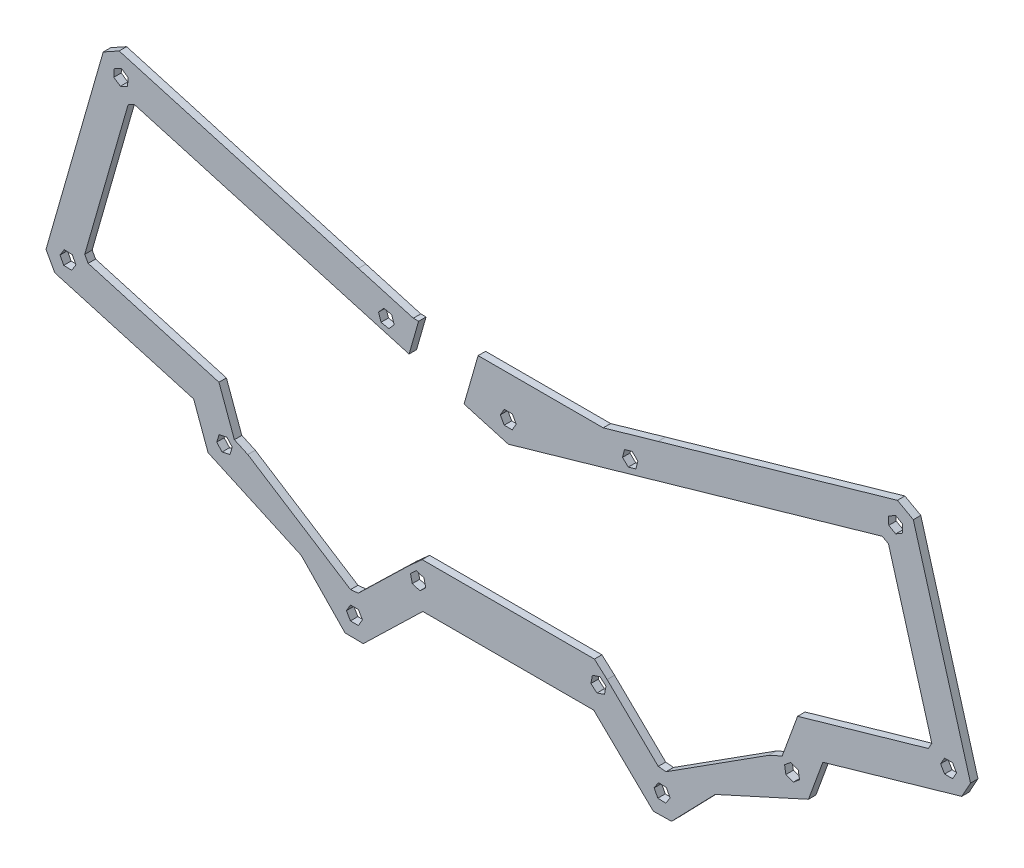
SolidWorks part; units mm, degrees
ref_plane "Plan de face" through (0, 0, 0) normal (0, 0, 1) x (1, 0, 0)
ref_plane "Plan de dessus" through (0, 0, 0) normal (0, 1, 0) x (1, 0, 0)
ref_plane "Plan de droite" through (0, 0, 0) normal (1, 0, 0) x (0, 0, -1)
sketch "Esquisse1" plane through (0, 0, 0) normal (0, 0, 1) x (1, 0, 0)
  line L0 (-121.6461, -32.0475) -> (-108.1875, -28.1884) construction
  line L1 (-108.1875, -28.1884) -> (-104.3283, -41.647) construction
  line L2 (-104.3283, -41.647) -> (-117.7869, -45.5062) construction
  line L3 (-117.7869, -45.5062) -> (-121.6461, -32.0475) construction
  line L4 (-100.1763, -37.9855) -> (-104.0355, -24.5269) construction
  line L5 (-104.0355, -24.5269) -> (-90.5769, -20.6677) construction
  line L6 (-90.5769, -20.6677) -> (-86.7177, -34.1263) construction
  line L7 (-86.7177, -34.1263) -> (-100.1763, -37.9855) construction
  line L8 (-82.5657, -30.4649) -> (-86.4249, -17.0063) construction
  line L9 (-86.4249, -17.0063) -> (-72.9663, -13.1471) construction
  line L10 (-72.9663, -13.1471) -> (-69.1071, -26.6057) construction
  line L11 (-69.1071, -26.6057) -> (-82.5657, -30.4649) construction
  line L12 (-63.6458, -27.5106) -> (-67.505, -14.0519) construction
  line L13 (-67.505, -14.0519) -> (-54.0463, -10.1927) construction
  line L14 (-54.0463, -10.1927) -> (-50.1872, -23.6514) construction
  line L15 (-50.1872, -23.6514) -> (-63.6458, -27.5106) construction
  line L16 (-44.0711, -26.8394) -> (-47.9303, -13.3808) construction
  line L17 (-47.9303, -13.3808) -> (-34.4717, -9.5216) construction
  line L18 (-34.4717, -9.5216) -> (-30.6125, -22.9802) construction
  line L19 (-30.6125, -22.9802) -> (-44.0711, -26.8394) construction
  line L20 (-25.8054, -21.6018) -> (-29.6646, -8.1432) construction
  line L21 (-29.6646, -8.1432) -> (-16.206, -4.284)
  line L22 (-16.206, -4.284) -> (-12.3468, -17.7426)
  line L23 (-12.3468, -17.7426) -> (-25.8054, -21.6018) construction
  line L24 (-116.4086, -50.3128) -> (-102.95, -46.4536) construction
  line L25 (-102.95, -46.4536) -> (-99.0908, -59.9122) construction
  line L26 (-99.0908, -59.9122) -> (-112.5494, -63.7714) construction
  line L27 (-112.5494, -63.7714) -> (-116.4086, -50.3128) construction
  line L28 (-98.798, -42.7922) -> (-85.3394, -38.933) construction
  line L29 (-85.3394, -38.933) -> (-81.4802, -52.3916) construction
  line L30 (-81.4802, -52.3916) -> (-94.9388, -56.2508) construction
  line L31 (-94.9388, -56.2508) -> (-98.798, -42.7922) construction
  line L32 (-81.1874, -35.2715) -> (-67.7288, -31.4123) construction
  line L33 (-67.7288, -31.4123) -> (-63.8696, -44.8709) construction
  line L34 (-63.8696, -44.8709) -> (-77.3282, -48.7301) construction
  line L35 (-77.3282, -48.7301) -> (-81.1874, -35.2715) construction
  line L36 (-62.2675, -32.3172) -> (-48.8089, -28.458) construction
  line L37 (-48.8089, -28.458) -> (-44.9497, -41.9166) construction
  line L38 (-44.9497, -41.9166) -> (-58.4083, -45.7758) construction
  line L39 (-58.4083, -45.7758) -> (-62.2675, -32.3172) construction
  line L40 (-42.6928, -31.646) -> (-29.2342, -27.7869) construction
  line L41 (-29.2342, -27.7869) -> (-25.375, -41.2455) construction
  line L42 (-25.375, -41.2455) -> (-38.8336, -45.1047) construction
  line L43 (-38.8336, -45.1047) -> (-42.6928, -31.646) construction
  line L44 (-24.4271, -26.4084) -> (-10.9685, -22.5492) construction
  line L45 (-10.9685, -22.5492) -> (-7.1093, -36.0078) construction
  line L46 (-7.1093, -36.0078) -> (-20.5679, -39.867) construction
  line L47 (-20.5679, -39.867) -> (-24.4271, -26.4084) construction
  line L48 (-19.1896, -44.6737) -> (-5.731, -40.8145) construction
  line L49 (-5.731, -40.8145) -> (-1.8718, -54.2731) construction
  line L50 (-1.8718, -54.2731) -> (-15.3304, -58.1323) construction
  line L51 (-15.3304, -58.1323) -> (-19.1896, -44.6737) construction
  line L52 (-37.4554, -49.9113) -> (-23.9967, -46.0521) construction
  line L53 (-23.9967, -46.0521) -> (-20.1376, -59.5107) construction
  line L54 (-20.1376, -59.5107) -> (-33.5962, -63.3699) construction
  line L55 (-33.5962, -63.3699) -> (-37.4554, -49.9113) construction
  line L56 (-57.03, -50.5825) -> (-43.5714, -46.7233) construction
  line L57 (-43.5714, -46.7233) -> (-39.7122, -60.1819) construction
  line L58 (-39.7122, -60.1819) -> (-53.1708, -64.0411) construction
  line L59 (-53.1708, -64.0411) -> (-57.03, -50.5825) construction
  line L60 (-75.9499, -53.5368) -> (-62.4913, -49.6776) construction
  line L61 (-62.4913, -49.6776) -> (-58.6321, -63.1362) construction
  line L62 (-58.6321, -63.1362) -> (-72.0908, -66.9954) construction
  line L63 (-72.0908, -66.9954) -> (-75.9499, -53.5368) construction
  line L64 (-93.5605, -61.0574) -> (-80.1019, -57.1982) construction
  line L65 (-80.1019, -57.1982) -> (-76.2427, -70.6569) construction
  line L66 (-76.2427, -70.6569) -> (-89.7013, -74.516) construction
  line L67 (-89.7013, -74.516) -> (-93.5605, -61.0574) construction
  line L68 (-111.1711, -68.5781) -> (-97.7125, -64.7189) construction
  line L69 (-97.7125, -64.7189) -> (-93.8533, -78.1775) construction
  line L70 (-93.8533, -78.1775) -> (-107.3119, -82.0367) construction
  line L71 (-107.3119, -82.0367) -> (-111.1711, -68.5781) construction
  line L72 (-79.0181, -77.3048) -> (-65.5595, -73.4456) construction
  line L73 (-65.5595, -73.4456) -> (-61.7003, -86.9042) construction
  line L74 (-61.7003, -86.9042) -> (-75.1589, -90.7634) construction
  line L75 (-75.1589, -90.7634) -> (-79.0181, -77.3048) construction
  line L76 (-99.4001, -88.1351) -> (-87.3916, -80.9362) construction
  line L77 (-87.3916, -80.9362) -> (-80.1927, -92.9448) construction
  line L78 (-80.1927, -92.9448) -> (-92.2012, -100.1436) construction
  line L79 (-92.2012, -100.1436) -> (-99.4001, -88.1351) construction
  line L80 (-120.0498, -100.4367) -> (-110.317, -90.3719) construction
  line L81 (-110.317, -90.3719) -> (-100.2522, -100.1047) construction
  line L82 (-100.2522, -100.1047) -> (-109.985, -110.1695) construction
  line L83 (-109.985, -110.1695) -> (-120.0498, -100.4367) construction
  line L86 (0.634, -55.7756) -> (-52.9527, -71.1413) construction
  line L89 (-59.2205, -88.2424) -> (-52.9527, -71.1413) construction
  line L96 (-93.4066, -103.0586) -> (-59.4637, -88.3612) construction
  line L97 (-105.418, -115.2057) -> (-93.9754, -103.3509) construction
  line L98 (-126.5332, -96.9919) -> (-107.5003, -115.385) construction
  line L99 (-167.7972, -50.1766) -> (-183.2082, -64.014) construction
  line L100 (-106.3822, -25.4572) -> (-123.6848, -30.4187) construction
  line L101 (-72.1178, -10.6906) -> (-88.4663, -15.3784) construction
  line L102 (-53.2337, -7.6163) -> (-70.5393, -12.5786) construction
  line L103 (-33.6604, -6.9452) -> (-50.9661, -11.9075) construction
  line L104 (-15.3965, -1.7081) -> (-31.745, -6.396) construction
  line L105 (0.5403, -55.2132) -> (-14.6896, -2.0999) construction
  line L106 (-16.199, -60.6113) -> (0.1495, -55.9235) construction
  line L107 (-52.7198, -71.0835) -> (-18.1144, -61.1606) construction
  line L108 (-59.1184, -88.0534) -> (-52.9674, -71.2752) construction
  line L109 (-183.2082, -64.014) -> (-173.1824, -64.9357) construction
  line L113 (-102.2678, -134.438) -> (-84.7238, -116.3191) construction
  line L114 (-84.7238, -116.3191) -> (-47.2969, -99.2981) construction
  line L115 (-47.2969, -99.2981) -> (-41.4917, -83.4594) construction
  line L116 (14.3812, -67.4381) -> (-41.4917, -83.4594) construction
  line L117 (17.8093, -61.2536) -> (-5.1371, 18.7701) construction
  line L122 (-11.3217, 22.1985) -> (-107.4545, -5.3614) construction
  line L129 (-167.7953, -27.6055) -> (-167.7953, -64.7189) construction
  line L130 (-242.0685, -103.8419) -> (-276.37, -88.2424) construction
  line L131 (-229.5108, -116.8112) -> (-242.0685, -103.8419) construction
  line L138 (-208.9328, -96.8551) -> (-229.5108, -116.8112) construction
  line L139 (-225.5107, -79.6567) -> (-208.9328, -96.8551) construction
  line L140 (-109.3352, -134.5492) -> (-102.2678, -134.438) construction
  line L142 (-5.1371, 18.7701) -> (-11.3217, 22.1985) construction
  line L143 (-211.4691, -30.6868) -> (-225.5107, -79.6567) construction
  line L147 (-114.18, -7.2899) -> (-107.4545, -5.3614) construction
  line L148 (-114.18, -7.2899) -> (-123.7936, -10.0465) construction
  line L154 (-4.3102, 15.8863) -> (-127.3606, -19.3904) construction
  line L155 (-131.531, -101.8802) -> (-105.9239, -126.7133) construction
  line L156 (-105.9239, -126.7133) -> (-89.4162, -109.6646) construction
  line L157 (-127.3539, -97.573) -> (-105.9069, -118.3718) construction
  line L158 (-105.9069, -118.3718) -> (-63.5032, -91.2886) construction
  line L159 (-63.5032, -91.2886) -> (-58.4256, -88.9794) construction
  line L160 (-58.4256, -88.9794) -> (-52.1886, -71.9625) construction
  line L161 (1.8709, -56.4612) -> (-52.1886, -71.9625) construction
  line L162 (1.8709, -56.4612) -> (-14.1861, -0.4639) construction
  line L163 (-14.1861, -0.4639) -> (-50.7166, -10.9388) construction
  line L164 (-50.7166, -10.9388) -> (-52.026, -6.3725) construction
  line L165 (-52.026, -6.3725) -> (-70.2913, -11.61) construction
  line L166 (-70.2913, -11.61) -> (-70.911, -9.4488) construction
  line L167 (-70.911, -9.4488) -> (-90.1377, -14.9608) construction
  line L168 (-90.1377, -14.9608) -> (-89.5177, -17.1231) construction
  line L169 (-89.5177, -17.1231) -> (-107.783, -22.3606) construction
  line L170 (-107.783, -22.3606) -> (-107.0938, -24.7639) construction
  line L171 (-107.0938, -24.7639) -> (-125.3583, -30.0011) construction
  line L172 (-125.3583, -30.0011) -> (-111.0411, -79.9324) construction
  line L173 (-110.7998, -78.9627) -> (-127.3777, -96.1611) construction
  line L174 (-89.4162, -109.6646) -> (-53.6562, -93.4017) construction
  line L175 (-53.6562, -93.4017) -> (-47.6042, -76.8897) construction
  line L176 (9.2923, -60.5749) -> (-47.6042, -76.8897) construction
  line L177 (9.2923, -60.5749) -> (-12.0005, 13.6817) construction
  line L178 (-229.7336, -25.4495) -> (-211.4691, -30.6868) construction
  line L179 (-229.0444, -23.0462) -> (-229.7336, -25.4495) construction
  line L180 (-173.1824, -64.9357) -> (-167.7972, -60.1004) construction
  line L181 (-247.3097, -17.8087) -> (-229.0444, -23.0462) construction
  line L185 (17.8093, -61.2536) -> (14.3812, -67.4381) construction
  line L186 (-183.2987, -65.7677) -> (-173.2729, -66.6895) construction
  line L187 (-173.2729, -66.6895) -> (-167.8052, -74.7882) construction
  line L190 (-246.6897, -15.6465) -> (-247.3097, -17.8087) construction
  line L191 (-263.9939, -10.6857) -> (-246.6897, -15.6465) construction
  line L192 (-264.6136, -12.8469) -> (-263.9939, -10.6857) construction
  line L193 (-282.8789, -7.6094) -> (-264.6136, -12.8469) construction
  line L194 (-284.1883, -12.1757) -> (-282.8789, -7.6094) construction
  line L195 (-320.7188, -1.7008) -> (-284.1883, -12.1757) construction
  line L196 (-336.2245, -55.7756) -> (-320.7188, -1.7008) construction
  line L197 (-183.2987, -65.7677) -> (-167.8052, -88.0782) construction
  line L198 (-181.8414, -71.5322) -> (-174.8684, -81.0171) construction
  line L199 (-174.8684, -81.0171) -> (-178.3549, -83.9622) construction
  line L200 (-344.8828, -60.5749) -> (-323.5901, 13.6817) construction
  line L201 (-344.8828, -60.5749) -> (-287.9863, -76.8897) construction
  line L202 (-281.9343, -93.4017) -> (-287.9863, -76.8897) construction
  line L203 (-246.1743, -109.6646) -> (-281.9343, -93.4017) construction
  line L204 (-224.7907, -78.9627) -> (-208.2128, -96.1611) construction
  line L205 (-210.2322, -30.0011) -> (-224.5494, -79.9324) construction
  line L206 (-228.4967, -24.7639) -> (-210.2322, -30.0011) construction
  line L207 (-227.8075, -22.3606) -> (-228.4967, -24.7639) construction
  line L208 (-246.0728, -17.1231) -> (-227.8075, -22.3606) construction
  line L209 (-245.4528, -14.9608) -> (-246.0728, -17.1231) construction
  line L210 (-264.6796, -9.4488) -> (-245.4528, -14.9608) construction
  line L211 (-265.2993, -11.61) -> (-264.6796, -9.4488) construction
  line L212 (-283.5645, -6.3725) -> (-265.2993, -11.61) construction
  line L213 (-284.8739, -10.9388) -> (-283.5645, -6.3725) construction
  line L217 (0.634, -55.7756) -> (-14.8717, -1.7008) construction
  line L220 (-14.8717, -1.7008) -> (-51.4022, -12.1757) construction
  line L221 (-51.4022, -12.1757) -> (-52.7116, -7.6094) construction
  line L222 (-52.7116, -7.6094) -> (-70.9769, -12.8469) construction
  line L223 (-70.9769, -12.8469) -> (-71.5966, -10.6857) construction
  line L224 (-71.5966, -10.6857) -> (-88.9008, -15.6465) construction
  line L225 (-88.9008, -15.6465) -> (-88.2808, -17.8087) construction
  line L226 (-88.2808, -17.8087) -> (-106.5461, -23.0462) construction
  line L227 (-106.5461, -23.0462) -> (-105.8569, -25.4495) construction
  line L228 (-105.8569, -25.4495) -> (-124.1214, -30.6868) construction
  line L231 (-124.1214, -30.6868) -> (-110.0799, -79.6567) construction
  line L232 (-110.0799, -79.6567) -> (-126.6577, -96.8551) construction
  line L233 (-126.6577, -96.8551) -> (-106.0797, -116.8112) construction
  line L234 (-106.0797, -116.8112) -> (-93.522, -103.8419) construction
  line L235 (-93.522, -103.8419) -> (-59.2205, -88.2424) construction
  line L236 (-321.4044, -0.4639) -> (-284.8739, -10.9388) construction
  line L237 (-337.4614, -56.4612) -> (-321.4044, -0.4639) construction
  line L238 (-337.4614, -56.4612) -> (-283.4019, -71.9625) construction
  line L239 (-277.1649, -88.9794) -> (-283.4019, -71.9625) construction
  line L240 (-272.0873, -91.2886) -> (-277.1649, -88.9794) construction
  line L241 (-229.6837, -118.3718) -> (-272.0873, -91.2886) construction
  line L242 (-208.2366, -97.573) -> (-229.6837, -118.3718) construction
  line L243 (-229.6666, -126.7133) -> (-246.1743, -109.6646) construction
  line L244 (-204.0596, -101.8802) -> (-229.6666, -126.7133) construction
  line L245 (-331.2803, 15.8863) -> (-208.2299, -19.3904) construction
  line L246 (-178.3549, -83.9622) -> (-185.8788, -75.0552) construction
  line L247 (-185.8788, -75.0552) -> (-181.8414, -71.5322) construction
  line L248 (-176.7625, -46.6332) -> (-185.5498, -54.5291) construction
  line L249 (-185.5498, -54.5291) -> (-181.1562, -59.4188) construction
  line L250 (-181.1562, -59.4188) -> (-172.3689, -51.5229) construction
  line L251 (-276.4721, -88.0534) -> (-282.6232, -71.2752) construction
  line L252 (-282.8707, -71.0835) -> (-317.4761, -61.1606) construction
  line L253 (-319.3915, -60.6113) -> (-335.74, -55.9235) construction
  line L254 (-336.1309, -55.2132) -> (-320.9009, -2.0999) construction
  line L255 (-320.194, -1.7081) -> (-303.8455, -6.396) construction
  line L256 (-301.9301, -6.9452) -> (-284.6245, -11.9075) construction
  line L257 (-282.3568, -7.6163) -> (-265.0512, -12.5786) construction
  line L258 (-263.4727, -10.6906) -> (-247.1242, -15.3784) construction
  line L259 (-229.2083, -25.4572) -> (-211.9057, -30.4187) construction
  line L260 (-172.3689, -51.5229) -> (-176.7625, -46.6332) construction
  line L261 (-209.0573, -96.9919) -> (-228.0902, -115.385) construction
  line L262 (-230.1725, -115.2057) -> (-241.6151, -103.3509) construction
  line L263 (-242.1839, -103.0586) -> (-276.1268, -88.3612) construction
  line L264 (-276.37, -88.2424) -> (-282.6379, -71.1413) construction
  line L265 (-336.2245, -55.7756) -> (-282.6379, -71.1413) construction
  line L268 (-353.3998, -61.2536) -> (-349.9717, -67.4381) construction
  line L274 (-221.4105, -7.2899) -> (-206.0252, -11.7015) construction
  line L275 (-221.4105, -7.2899) -> (-228.136, -5.3614) construction
  line L276 (-330.4534, 18.7701) -> (-324.2688, 22.1985) construction
  line L277 (-226.2553, -134.5492) -> (-233.3227, -134.438) construction
  line L281 (-324.2688, 22.1985) -> (-228.136, -5.3614) construction
  line L282 (-353.3998, -61.2536) -> (-330.4534, 18.7701) construction
  line L283 (-349.9717, -67.4381) -> (-294.0988, -83.4594) construction
  line L284 (-288.2936, -99.2981) -> (-294.0988, -83.4594) construction
  line L285 (-250.8667, -116.3191) -> (-288.2936, -99.2981) construction
  line L286 (-233.3227, -134.438) -> (-250.8667, -116.3191) construction
  line L288 (-225.6055, -110.1695) -> (-215.5407, -100.4367) construction
  line L289 (-235.3383, -100.1047) -> (-225.6055, -110.1695) construction
  line L290 (-225.2735, -90.3719) -> (-235.3383, -100.1047) construction
  line L291 (-215.5407, -100.4367) -> (-225.2735, -90.3719) construction
  line L292 (-243.3893, -100.1436) -> (-236.1904, -88.1351) construction
  line L293 (-255.3978, -92.9448) -> (-243.3893, -100.1436) construction
  line L294 (-248.1989, -80.9362) -> (-255.3978, -92.9448) construction
  line L295 (-236.1904, -88.1351) -> (-248.1989, -80.9362) construction
  line L296 (-260.4316, -90.7634) -> (-256.5724, -77.3048) construction
  line L297 (-273.8902, -86.9042) -> (-260.4316, -90.7634) construction
  line L298 (-270.031, -73.4456) -> (-273.8902, -86.9042) construction
  line L299 (-256.5724, -77.3048) -> (-270.031, -73.4456) construction
  line L300 (-228.2786, -82.0367) -> (-224.4194, -68.5781) construction
  line L301 (-241.7372, -78.1775) -> (-228.2786, -82.0367) construction
  line L302 (-237.878, -64.7189) -> (-241.7372, -78.1775) construction
  line L303 (-224.4194, -68.5781) -> (-237.878, -64.7189) construction
  line L304 (-245.8892, -74.516) -> (-242.03, -61.0574) construction
  line L305 (-259.3478, -70.6569) -> (-245.8892, -74.516) construction
  line L306 (-255.4886, -57.1982) -> (-259.3478, -70.6569) construction
  line L307 (-242.03, -61.0574) -> (-255.4886, -57.1982) construction
  line L308 (-263.4998, -66.9954) -> (-259.6406, -53.5368) construction
  line L309 (-276.9584, -63.1362) -> (-263.4998, -66.9954) construction
  line L310 (-273.0992, -49.6776) -> (-276.9584, -63.1362) construction
  line L311 (-259.6406, -53.5368) -> (-273.0992, -49.6776)
  line L312 (-282.4197, -64.0411) -> (-278.5605, -50.5825) construction
  line L313 (-295.8783, -60.1819) -> (-282.4197, -64.0411) construction
  line L314 (-292.0191, -46.7233) -> (-295.8783, -60.1819) construction
  line L315 (-278.5605, -50.5825) -> (-292.0191, -46.7233) construction
  line L316 (-301.9944, -63.3699) -> (-298.1352, -49.9113) construction
  line L317 (-315.453, -59.5107) -> (-301.9944, -63.3699) construction
  line L318 (-311.5938, -46.0521) -> (-315.453, -59.5107) construction
  line L319 (-298.1352, -49.9113) -> (-311.5938, -46.0521) construction
  line L320 (-320.2601, -58.1323) -> (-316.4009, -44.6737) construction
  line L321 (-333.7187, -54.2731) -> (-320.2601, -58.1323) construction
  line L322 (-329.8595, -40.8145) -> (-333.7187, -54.2731) construction
  line L323 (-316.4009, -44.6737) -> (-329.8595, -40.8145) construction
  line L324 (-315.0226, -39.867) -> (-311.1634, -26.4084) construction
  line L325 (-328.4812, -36.0078) -> (-315.0226, -39.867) construction
  line L326 (-324.622, -22.5492) -> (-328.4812, -36.0078) construction
  line L327 (-311.1634, -26.4084) -> (-324.622, -22.5492) construction
  line L328 (-296.7569, -45.1047) -> (-292.8977, -31.646) construction
  line L329 (-310.2155, -41.2455) -> (-296.7569, -45.1047) construction
  line L330 (-306.3563, -27.7869) -> (-310.2155, -41.2455) construction
  line L331 (-292.8977, -31.646) -> (-306.3563, -27.7869) construction
  line L332 (-277.1822, -45.7758) -> (-273.323, -32.3172) construction
  line L333 (-290.6408, -41.9166) -> (-277.1822, -45.7758) construction
  line L334 (-286.7817, -28.458) -> (-290.6408, -41.9166) construction
  line L335 (-273.323, -32.3172) -> (-286.7817, -28.458) construction
  line L336 (-258.2623, -48.7301) -> (-254.4031, -35.2715) construction
  line L337 (-271.7209, -44.8709) -> (-258.2623, -48.7301) construction
  line L338 (-267.8617, -31.4123) -> (-271.7209, -44.8709) construction
  line L339 (-254.4031, -35.2715) -> (-267.8617, -31.4123) construction
  line L340 (-240.6517, -56.2508) -> (-236.7925, -42.7922) construction
  line L341 (-254.1103, -52.3916) -> (-240.6517, -56.2508) construction
  line L342 (-250.2511, -38.933) -> (-254.1103, -52.3916) construction
  line L343 (-236.7925, -42.7922) -> (-250.2511, -38.933) construction
  line L344 (-223.0411, -63.7714) -> (-219.1819, -50.3128) construction
  line L345 (-236.4997, -59.9122) -> (-223.0411, -63.7714) construction
  line L346 (-232.6405, -46.4536) -> (-236.4997, -59.9122) construction
  line L347 (-219.1819, -50.3128) -> (-232.6405, -46.4536) construction
  line L348 (-323.2438, -17.7426) -> (-309.7851, -21.6018) construction
  line L349 (-319.3846, -4.284) -> (-323.2438, -17.7426) construction
  line L350 (-305.926, -8.1432) -> (-319.3846, -4.284) construction
  line L351 (-309.7851, -21.6018) -> (-305.926, -8.1432) construction
  line L352 (-304.978, -22.9802) -> (-291.5194, -26.8394) construction
  line L353 (-301.1188, -9.5216) -> (-304.978, -22.9802) construction
  line L354 (-287.6602, -13.3808) -> (-301.1188, -9.5216) construction
  line L355 (-291.5194, -26.8394) -> (-287.6602, -13.3808) construction
  line L356 (-285.4034, -23.6514) -> (-271.9448, -27.5106) construction
  line L357 (-281.5442, -10.1927) -> (-285.4034, -23.6514) construction
  line L358 (-268.0856, -14.0519) -> (-281.5442, -10.1927) construction
  line L359 (-271.9448, -27.5106) -> (-268.0856, -14.0519) construction
  line L360 (-266.4834, -26.6057) -> (-253.0248, -30.4649) construction
  line L361 (-262.6242, -13.1471) -> (-266.4834, -26.6057) construction
  line L362 (-249.1656, -17.0063) -> (-262.6242, -13.1471) construction
  line L363 (-253.0248, -30.4649) -> (-249.1656, -17.0063) construction
  line L364 (-248.8728, -34.1263) -> (-235.4142, -37.9855) construction
  line L365 (-245.0136, -20.6677) -> (-248.8728, -34.1263) construction
  line L366 (-231.555, -24.5269) -> (-245.0136, -20.6677) construction
  line L367 (-235.4142, -37.9855) -> (-231.555, -24.5269) construction
  line L368 (-217.8036, -45.5062) -> (-213.9444, -32.0475) construction
  line L369 (-231.2622, -41.647) -> (-217.8036, -45.5062) construction
  line L370 (-227.4031, -28.1884) -> (-231.2622, -41.647) construction
  line L371 (-213.9444, -32.0475) -> (-227.4031, -28.1884) construction
  line L372 (-226.2553, -134.5492) -> (-202.2968, -111.3509) construction
  line L373 (-109.3352, -134.5492) -> (-133.2937, -111.3509) construction
  line L374 (-141.5559, -103.3509) -> (-194.0347, -103.3509) construction
  line L375 (-167.7972, -50.1766) -> (-152.3861, -64.014) construction
  line L376 (-162.4119, -64.9357) -> (-167.7972, -60.1004) construction
  line L377 (-162.3376, -66.6895) -> (-167.8052, -74.7882) construction
  line L378 (-152.3118, -65.7677) -> (-167.8052, -88.0782) construction
  line L379 (-163.2254, -51.5229) -> (-158.8318, -46.6332) construction
  line L380 (-154.4381, -59.4188) -> (-163.2254, -51.5229) construction
  line L381 (-150.0445, -54.5291) -> (-154.4381, -59.4188) construction
  line L382 (-158.8318, -46.6332) -> (-150.0445, -54.5291) construction
  line L383 (-149.7316, -75.0552) -> (-153.7691, -71.5322) construction
  line L384 (-157.2555, -83.9622) -> (-149.7316, -75.0552) construction
  line L385 (-160.742, -81.0171) -> (-157.2555, -83.9622) construction
  line L386 (-153.7691, -71.5322) -> (-160.742, -81.0171) construction
  line L387 (-152.3118, -65.7677) -> (-162.3376, -66.6895) construction
  line L388 (-152.3861, -64.014) -> (-162.4119, -64.9357) construction
  line L389 (-206.0252, -11.7015) -> (-129.5654, -11.7015) construction
  line L390 (-119.0708, -62.7964) -> (-130.6498, -22.4155) construction
  line L391 (-123.5545, -47.16) -> (-127.4136, -33.7014) construction
  line L392 (-120.442, -65.2702) -> (-138.2688, -70.3819) construction
  line L393 (-140.7426, -69.0107) -> (-154.4194, -21.3141) construction
  line L394 (-167.1758, -11.7015) -> (-206.0252, -11.7015) construction
  line L395 (-156.8153, -19.5087) -> (-167.1758, -11.7015) construction
  line L396 (-123.7936, -10.0465) -> (-130.6498, -22.4155) construction
  line L397 (-138.2688, -70.3819) -> (-140.7426, -69.0107) construction
  line L398 (-119.0708, -62.7964) -> (-120.442, -65.2702) construction
  line L399 (-129.5654, -11.7015) -> (-123.7936, -10.0465) construction
  line L400 (-207.5404, -98.2908) -> (-228.1196, -118.248)
  line L401 (-231.2409, -118.5638) -> (-272.5658, -92.1695)
  line L402 (-272.5658, -92.1695) -> (-277.9598, -89.7165)
  line L403 (-277.9598, -89.7165) -> (-284.166, -72.7837)
  line L404 (-336.7758, -57.6981) -> (-284.166, -72.7837)
  line L405 (-338.147, -55.2243) -> (-320.7131, 5.5749)
  line L406 (-223.5881, -80.208) -> (-202.439, -93.7159) construction
  line L407 (-202.439, -93.7159) -> (-207.5404, -98.2908)
  line L408 (-17.3512, 6.9463) -> (-127.905, -24.7479)
  line L409 (2.5565, -55.2243) -> (-14.8774, 5.5749)
  line L410 (-318.2393, 6.9463) -> (-207.6856, -24.7479)
  line L411 (1.1853, -57.6981) -> (-51.4245, -72.7837)
  line L412 (-57.6307, -89.7165) -> (-51.4245, -72.7837)
  line L413 (-63.0247, -92.1695) -> (-57.6307, -89.7165)
  line L414 (-104.3497, -118.5638) -> (-63.0247, -92.1695)
  line L415 (-203.9447, -11.7015) -> (-223.5881, -80.208) construction
  line L416 (-338.6983, -57.1468) -> (-322.0901, 0.773) construction
  line L417 (-265.3652, -8.212) -> (-244.2159, -14.2752) construction
  line L418 (-208.9953, -29.3155) -> (-223.5881, -80.208) construction
  line L419 (-227.2598, -24.0783) -> (-208.9953, -29.3155) construction
  line L420 (-226.5706, -21.6749) -> (-227.2598, -24.0783) construction
  line L421 (-244.8359, -16.4375) -> (-226.5706, -21.6749) construction
  line L422 (-244.2159, -14.2752) -> (-244.8359, -16.4375) construction
  line L423 (-265.9849, -10.3731) -> (-265.3652, -8.212) construction
  line L424 (-284.2502, -5.1356) -> (-265.9849, -10.3731) construction
  line L425 (-285.5595, -9.7019) -> (-284.2502, -5.1356) construction
  line L426 (-322.0901, 0.773) -> (-285.5595, -9.7019) construction
  line L427 (-128.0501, -98.2908) -> (-107.4709, -118.248)
  line L428 (-133.1515, -93.7159) -> (-128.0501, -98.2908)
  line L429 (-127.905, -24.7479) -> (-167.7953, -36.1862) construction
  line L431 (-202.439, -93.7159) -> (-133.1515, -93.7159)
  line L433 (-167.7911, -36.185) -> (-127.905, -24.7479)
  line L435 (-320.7131, 5.5749) -> (-318.2393, 6.9463)
  line L436 (-338.6983, -57.1468) -> (-284.166, -72.7837) construction
  line L437 (-338.147, -55.2243) -> (-336.7758, -57.6981)
  line L438 (-207.5404, -98.2908) -> (-229.5553, -119.6404) construction
  line L439 (-229.5553, -119.6404) -> (-272.5658, -92.1695) construction
  line L440 (-228.1196, -118.248) -> (-231.2409, -118.5638)
  line L441 (-107.4709, -118.248) -> (-104.3497, -118.5638)
  line L442 (2.5565, -55.2243) -> (1.1853, -57.6981)
  line L443 (-14.8774, 5.5749) -> (-17.3512, 6.9463)
  line L444 (-133.2937, -111.3509) -> (-202.2968, -111.3509) construction
  line L445 (-214.6968, -14.5277) -> (-217.8401, -13.8763)
  line L446 (-217.8401, -13.8763) -> (-219.9759, -16.2728)
  line L447 (-219.9759, -16.2728) -> (-218.9683, -19.3206)
  line L448 (-218.9683, -19.3206) -> (-215.8251, -19.972)
  line L449 (-215.8251, -19.972) -> (-213.6893, -17.5755)
  line L450 (-213.6893, -17.5755) -> (-214.6968, -14.5277)
  line L451 (-166.1757, -24.834) -> (-169.3858, -24.8172)
  line L452 (-169.3858, -24.8172) -> (-171.0053, -27.5888)
  line L453 (-171.0053, -27.5888) -> (-169.4148, -30.3771)
  line L454 (-169.4148, -30.3771) -> (-166.2047, -30.3939)
  line L455 (-166.2047, -30.3939) -> (-164.5852, -27.6223)
  line L456 (-164.5852, -27.6223) -> (-166.1757, -24.834)
  line L457 (-115.6722, -16.0395) -> (-117.9812, -13.8095)
  line L458 (-117.9812, -13.8095) -> (-121.0669, -14.6941)
  line L459 (-121.0669, -14.6941) -> (-121.8437, -17.8088)
  line L460 (-121.8437, -17.8088) -> (-119.5347, -20.0388)
  line L461 (-119.5347, -20.0388) -> (-116.4489, -19.1542)
  line L462 (-116.4489, -19.1542) -> (-115.6722, -16.0395)
  line L463 (-9.2401, 15.3202) -> (-12.0393, 16.8915)
  line L464 (-12.0393, 16.8915) -> (-14.7996, 15.253)
  line L465 (-14.7996, 15.253) -> (-14.7608, 12.0431)
  line L466 (-14.7608, 12.0431) -> (-11.9616, 10.4718)
  line L467 (-11.9616, 10.4718) -> (-9.2013, 12.1103)
  line L468 (-9.2013, 12.1103) -> (-9.2401, 15.3202)
  line L469 (12.5024, -60.5749) -> (10.8973, -57.7949)
  line L470 (10.8973, -57.7949) -> (7.6873, -57.7949)
  line L471 (7.6873, -57.7949) -> (6.0822, -60.5749)
  line L472 (6.0822, -60.5749) -> (7.6873, -63.3549)
  line L473 (7.6873, -63.3549) -> (10.8973, -63.3549)
  line L474 (10.8973, -63.3549) -> (12.5024, -60.5749)
  line L475 (-50.6498, -94.5269) -> (-51.1786, -91.3606)
  line L476 (-51.1786, -91.3606) -> (-54.185, -90.2355)
  line L477 (-54.185, -90.2355) -> (-56.6626, -92.2765)
  line L478 (-56.6626, -92.2765) -> (-56.1338, -95.4427)
  line L479 (-56.1338, -95.4427) -> (-53.1274, -96.5679)
  line L480 (-53.1274, -96.5679) -> (-50.6498, -94.5269)
  line L481 (-104.4402, -129.5599) -> (-102.7168, -126.8517)
  line L482 (-102.7168, -126.8517) -> (-104.2006, -124.0051)
  line L483 (-104.2006, -124.0051) -> (-107.4076, -123.8667)
  line L484 (-107.4076, -123.8667) -> (-109.131, -126.575)
  line L485 (-109.131, -126.575) -> (-107.6473, -129.4216)
  line L486 (-107.6473, -129.4216) -> (-104.4402, -129.5599)
  line L487 (-132.1348, -105.033) -> (-129.1025, -103.9795)
  line L488 (-129.1025, -103.9795) -> (-128.4987, -100.8268)
  line L489 (-128.4987, -100.8268) -> (-130.9271, -98.7274)
  line L490 (-130.9271, -98.7274) -> (-133.9594, -99.7809)
  line L491 (-133.9594, -99.7809) -> (-134.5633, -102.9336)
  line L492 (-134.5633, -102.9336) -> (-132.1348, -105.033)
  line L493 (-200.9863, -102.8073) -> (-201.7201, -99.6822)
  line L494 (-201.7201, -99.6822) -> (-204.7933, -98.7551)
  line L495 (-204.7933, -98.7551) -> (-207.1328, -100.9531)
  line L496 (-207.1328, -100.9531) -> (-206.3991, -104.0782)
  line L497 (-206.3991, -104.0782) -> (-203.3258, -105.0053)
  line L498 (-203.3258, -105.0053) -> (-200.9863, -102.8073)
  line L499 (-228.0726, -129.4997) -> (-226.4565, -126.726)
  line L500 (-226.4565, -126.726) -> (-228.0506, -123.9397)
  line L501 (-228.0506, -123.9397) -> (-231.2606, -123.927)
  line L502 (-231.2606, -123.927) -> (-232.8766, -126.7006)
  line L503 (-232.8766, -126.7006) -> (-231.2826, -129.4869)
  line L504 (-231.2826, -129.4869) -> (-228.0726, -129.4997)
  line L505 (-279.7615, -95.7646) -> (-278.8016, -92.7014)
  line L506 (-278.8016, -92.7014) -> (-280.9744, -90.3385)
  line L507 (-280.9744, -90.3385) -> (-284.1072, -91.0388)
  line L508 (-284.1072, -91.0388) -> (-285.0671, -94.102)
  line L509 (-285.0671, -94.102) -> (-282.8943, -96.4649)
  line L510 (-282.8943, -96.4649) -> (-279.7615, -95.7646)
  line L511 (-343.3818, -63.4124) -> (-341.6749, -60.6938)
  line L512 (-341.6749, -60.6938) -> (-343.176, -57.8563)
  line L513 (-343.176, -57.8563) -> (-346.3838, -57.7374)
  line L514 (-346.3838, -57.7374) -> (-348.0907, -60.4561)
  line L515 (-348.0907, -60.4561) -> (-346.5896, -63.2936)
  line L516 (-346.5896, -63.2936) -> (-343.3818, -63.4124)
  line L517 (-323.3776, 16.8847) -> (-326.2578, 15.4671)
  line L518 (-326.2578, 15.4671) -> (-326.4702, 12.2641)
  line L519 (-326.4702, 12.2641) -> (-323.8025, 10.4786)
  line L520 (-323.8025, 10.4786) -> (-320.9224, 11.8962)
  line L521 (-320.9224, 11.8962) -> (-320.7099, 15.0992)
  line L522 (-320.7099, 15.0992) -> (-323.3776, 16.8847)
  line L523 (-141.5559, -111.3509) -> (-194.0347, -111.3509) construction
  line L524 (-129.6075, -11.4015) -> (-179.9318, -11.4015)
  line L525 (-221.3278, -7.0015) -> (-205.983, -11.4015)
  line L526 (-221.3278, -7.0015) -> (-228.0533, -5.073)
  line L527 (-324.3056, 22.5211) -> (-228.0533, -5.073)
  line L528 (-330.7075, 18.9723) -> (-324.3056, 22.5211)
  line L529 (-353.7224, -61.2904) -> (-330.7075, 18.9723)
  line L530 (-353.7224, -61.2904) -> (-350.1738, -67.6922)
  line L531 (-350.1738, -67.6922) -> (-294.328, -83.7058)
  line L532 (-288.5321, -99.5192) -> (-294.328, -83.7058)
  line L533 (-251.0427, -116.5686) -> (-288.5321, -99.5192)
  line L534 (-233.4517, -134.736) -> (-251.0427, -116.5686)
  line L535 (-226.1358, -134.8511) -> (-233.4517, -134.736)
  line L536 (-226.1358, -134.8511) -> (-202.1754, -111.6509)
  line L537 (-133.4151, -111.6509) -> (-202.1754, -111.6509)
  line L538 (-109.4547, -134.8511) -> (-133.4151, -111.6509)
  line L539 (-109.4547, -134.8511) -> (-102.1388, -134.736)
  line L540 (-102.1388, -134.736) -> (-84.5479, -116.5686)
  line L541 (-84.5479, -116.5686) -> (-47.0584, -99.5192)
  line L542 (-47.0584, -99.5192) -> (-41.2625, -83.7058)
  line L543 (14.5833, -67.6922) -> (-41.2625, -83.7058)
  line L544 (18.1319, -61.2904) -> (14.5833, -67.6922)
  line L545 (18.1319, -61.2904) -> (-4.883, 18.9723)
  line L546 (-4.883, 18.9723) -> (-11.2849, 22.5211)
  line L547 (-11.2849, 22.5211) -> (-107.5372, -5.073)
  line L548 (-114.2627, -7.0015) -> (-107.5372, -5.073)
  line L549 (-114.2627, -7.0015) -> (-129.6075, -11.4015)
  line L550 (-167.1758, -11.4015) -> (-166.7924, -11.7015)
  line L551 (-124.0736, -10.1268) -> (-123.8763, -9.7581)
  line L552 (-167.1758, -11.4015) -> (-205.983, -11.4015) construction
  line L553 (-114.2627, -7.0015) -> (-123.8763, -9.7581) construction
  line L554 (-207.6856, -24.7479) -> (-203.8587, -11.4015)
  line L555 (-185.5765, -31.0874) -> (-179.9318, -11.4015)
  line L556 (-185.5765, -31.0874) -> (-181.7496, -17.7411) construction
  line L557 (-203.8587, -11.4015) -> (-205.983, -11.4015)
  line L558 (-185.5762, -31.0863) -> (-167.7911, -36.185)
  circle A2 centre (-12.0005, 13.6817) radius 1.6 construction
  circle A3 centre (-12.0005, 13.6817) radius 3 construction
  circle A4 centre (-118.7579, -16.9241) radius 1.6 construction
  circle A5 centre (9.2923, -60.5749) radius 1.6 construction
  circle A6 centre (-53.6562, -93.4017) radius 1.6 construction
  circle A7 centre (-105.9239, -126.7133) radius 1.6 construction
  circle A8 centre (-131.531, -101.8802) radius 1.6 construction
  circle A10 centre (-147.4897, -45.973) radius 1.6 construction
  circle A11 centre (-323.5901, 13.6817) radius 3 construction
  circle A12 centre (-188.1008, -45.973) radius 1.6 construction
  circle A14 centre (-204.0596, -101.8802) radius 1.6 construction
  circle A15 centre (-229.6666, -126.7133) radius 1.6 construction
  circle A16 centre (-281.9343, -93.4017) radius 1.6 construction
  circle A17 centre (-344.8828, -60.5749) radius 1.6 construction
  circle A18 centre (-216.8326, -16.9241) radius 1.6 construction
  circle A19 centre (-323.5901, 13.6817) radius 1.6 construction
  circle A20 centre (-167.7953, -27.6055) radius 1.6 construction
  circle A21 centre (-216.8326, -16.9241) radius 2.78 construction
  circle A22 centre (-167.7953, -27.6055) radius 2.78 construction
  circle A23 centre (-118.7579, -16.9241) radius 2.78 construction
  circle A24 centre (-12.0005, 13.6817) radius 2.78 construction
  circle A25 centre (9.2923, -60.5749) radius 2.78 construction
  circle A26 centre (-53.6562, -93.4017) radius 2.78 construction
  circle A27 centre (-105.9239, -126.7133) radius 2.78 construction
  circle A28 centre (-131.531, -101.8802) radius 2.78 construction
  circle A29 centre (-204.0596, -101.8802) radius 2.78 construction
  circle A30 centre (-229.6666, -126.7133) radius 2.78 construction
  circle A31 centre (-281.9343, -93.4017) radius 2.78 construction
  circle A32 centre (-344.8828, -60.5749) radius 2.78 construction
  circle A33 centre (-323.5901, 13.6817) radius 2.78 construction
  point P138 (-167.7953, -27.6055)
  point P139 (-6.5153, 23.5764)
  point P150 (-169.1046, -23.0392)
  point P200 (19.1875, -66.0599)
  point P203 (-141.5228, -71.3355)
  point P204 (-141.5228, 1.5705)
  point P263 (-133.4062, -12.8029)
  point P264 (-118.5195, -64.7189)
  point P283 (-140.1914, -70.9332)
  point P284 (-157.1758, -11.7015)
  point P405 (-354.778, -66.0599)
  point P406 (-329.0752, 23.5764)
  point P423 (-15.4286, 7.4974)
  point P424 (-320.1619, 7.4974)
  point P429 (3.1078, -57.1468)
  point P434 (-106.0352, -119.6404)
  dimension "D3" = 3.2
  dimension "D4" = 6
  dimension "D6" = 3.2
  dimension "D7" = 3.2
  dimension "D8" = 3.2
  dimension "D9" = 3.2
  dimension "D10" = 3.2
  dimension "D16" = 3.2
  dimension "D21" = 5.56
  dimension "D34" = 5.56
  dimension "D2" = 6
  dimension "D5" = 1
  dimension "D37" = 23
  dimension "D11" = 5.56
  dimension "D14" = 5.56
  dimension "D22" = 5.56
  dimension "D26" = 5.56
  dimension "D27" = 5.56
  dimension "D28" = 5.56
  dimension "D29" = 5.56
  dimension "D30" = 5.56
  dimension "D31" = 5.56
  dimension "D32" = 5.56
  dimension "D33" = 5.56
  dimension "D35" = 8
  dimension "D36" = 0.3
extrude "Boss.-Extru.1" add sketch "Esquisse1" along normal blind 3
